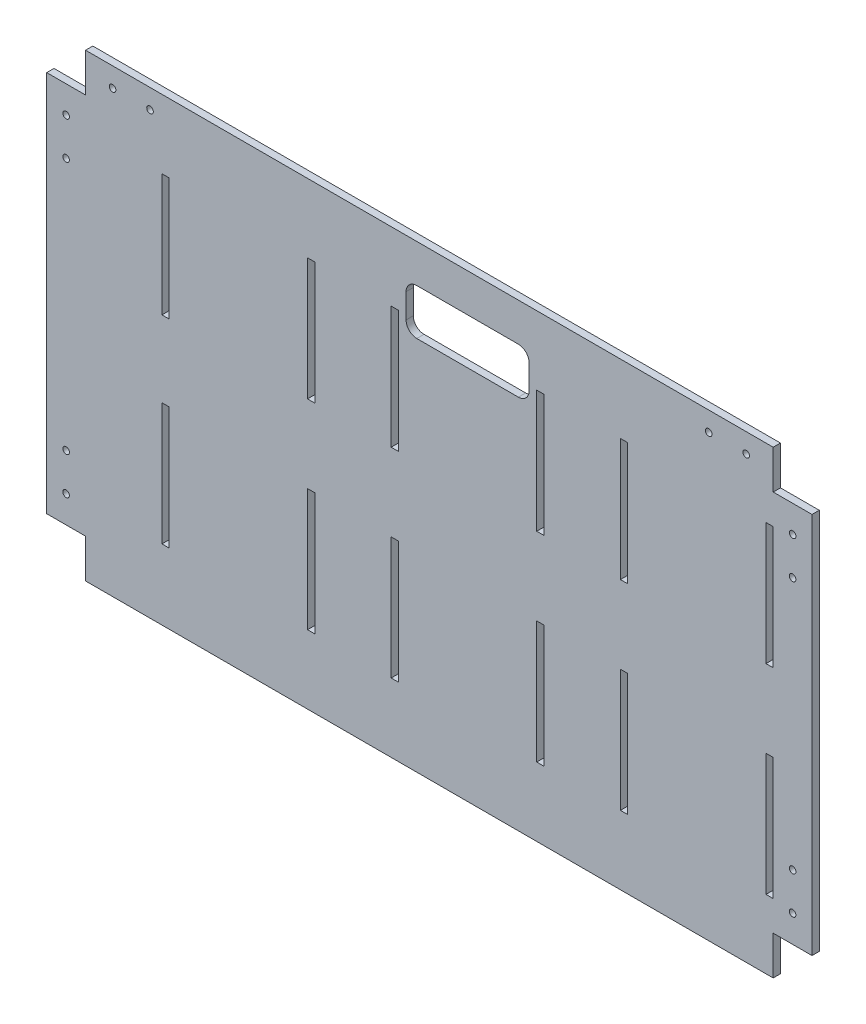
SolidWorks part; units mm, degrees
ref_plane "前基準面" through (0, 0, 0) normal (0, 0, 1) x (1, 0, 0)
ref_plane "上基準面" through (0, 0, 0) normal (0, 1, 0) x (1, 0, 0)
ref_plane "右基準面" through (0, 0, 0) normal (1, 0, 0) x (0, 0, -1)
sketch "草圖1" plane through (0, 0, 0) normal (0, 0, 1) x (1, 0, 0)
  line L1 (-250.4, 150.4) -> (250.4, 150.4)
  line L2 (-250.4, 150.4) -> (-250.4, -150.4)
  line L3 (-250.4, -150.4) -> (250.4, -150.4)
  line L4 (250.4, 150.4) -> (250.4, -150.4)
  line L5 (-250.4, 150.4) -> (250.4, -150.4) construction
  line L6 (-250.4, -150.4) -> (250.4, 150.4) construction
  point P0 (0, 0)
  dimension "D1" = 500.8
  dimension "D2" = 300.8
extrude "填料-伸長1" add sketch "草圖1" along normal blind 4.75 contours L1 L4 L3 L2
sketch "草圖2" plane through (0, 0, 0) normal (0, 0, -1) x (-1, 0, 0)
  line L0 (-225, 125) -> (-225, -125) construction
  line L1 (-250.4, 150.4) -> (-225, 150.4)
  line L2 (-250.4, 150.4) -> (-250.4, 125)
  line L3 (-250.4, 125) -> (-225, 125)
  line L4 (-225, 150.4) -> (-225, 125)
  line L5 (-250.4, -150.4) -> (-225, -150.4)
  line L6 (-250.4, -150.4) -> (-250.4, -125)
  line L7 (-250.4, -125) -> (-225, -125)
  line L8 (-225, -150.4) -> (-225, -125)
  line L9 (250.4, 150.4) -> (225, 150.4)
  line L10 (250.4, 150.4) -> (250.4, 125)
  line L12 (225, 150.4) -> (225, 125)
  line L13 (250.4, -150.4) -> (225, -150.4)
  line L14 (250.4, -150.4) -> (250.4, -125)
  line L16 (225, -150.4) -> (225, -125)
  line L18 (250.4, 150.4) -> (-250.4, 150.4) construction
  line L19 (-225, 105.4) -> (-220.25, 105.4)
  line L20 (-225, 105.4) -> (-225, 25.4)
  line L21 (-225, 25.4) -> (-220.25, 25.4)
  line L22 (-220.25, 105.4) -> (-220.25, 25.4)
  line L23 (-225, -25.4) -> (-220.25, -25.4)
  line L24 (-225, -25.4) -> (-225, -105.4)
  line L25 (-225, -105.4) -> (-220.25, -105.4)
  line L26 (-220.25, -25.4) -> (-220.25, -105.4)
  line L27 (250.4, -150.4) -> (-250.4, -150.4) construction
  line L44 (175, 105.4) -> (175, 25.4)
  line L45 (175, 105.4) -> (170.25, 105.4)
  line L46 (170.25, 105.4) -> (170.25, 25.4)
  line L47 (175, 25.4) -> (170.25, 25.4)
  line L48 (175, -24.4) -> (175, -104.4)
  line L49 (175, -24.4) -> (170.25, -24.4)
  line L50 (170.25, -24.4) -> (170.25, -104.4)
  line L51 (175, -104.4) -> (170.25, -104.4)
  line L52 (-129.75, 105.4) -> (-129.75, 25.4)
  line L53 (-129.75, 25.4) -> (-125, 25.4)
  line L54 (-125, 105.4) -> (-125, 25.4)
  line L55 (-129.75, 105.4) -> (-125, 105.4)
  line L60 (-75, 105.4) -> (-75, 25.4)
  line L61 (-75, 25.4) -> (-70.25, 25.4)
  line L62 (-70.25, 105.4) -> (-70.25, 25.4)
  line L63 (-75, 105.4) -> (-70.25, 105.4)
  line L68 (20.25, 105.4) -> (20.25, 25.4)
  line L69 (20.25, 25.4) -> (25, 25.4)
  line L70 (25, 105.4) -> (25, 25.4)
  line L71 (20.25, 105.4) -> (25, 105.4)
  line L80 (75, 105.4) -> (75, 25.4)
  line L81 (75, 25.4) -> (79.75, 25.4)
  line L82 (79.75, 105.4) -> (79.75, 25.4)
  line L83 (75, 105.4) -> (79.75, 105.4)
  line L84 (-250.4, 0) -> (250.4, 0) construction
  line L85 (-250.4, 150.4) -> (-250.4, -150.4) construction
  line L86 (250.4, 150.4) -> (250.4, -150.4) construction
  line L89 (250.4, -125) -> (250.4, 125)
  line L91 (250.4, 125) -> (250.4, -125)
  line L92 (75, -105.4) -> (79.75, -105.4)
  line L93 (79.75, -105.4) -> (79.75, -25.4)
  line L94 (75, -25.4) -> (79.75, -25.4)
  line L95 (75, -105.4) -> (75, -25.4)
  line L96 (20.25, -105.4) -> (25, -105.4)
  line L97 (25, -105.4) -> (25, -25.4)
  line L98 (20.25, -25.4) -> (25, -25.4)
  line L99 (20.25, -105.4) -> (20.25, -25.4)
  line L101 (-129.75, -105.4) -> (-125, -105.4)
  line L102 (-125, -105.4) -> (-125, -25.4)
  line L103 (-129.75, -25.4) -> (-125, -25.4)
  line L104 (-129.75, -105.4) -> (-129.75, -25.4)
  line L105 (-75, -105.4) -> (-70.25, -105.4)
  line L106 (-70.25, -105.4) -> (-70.25, -25.4)
  line L107 (-75, -25.4) -> (-70.25, -25.4)
  line L108 (-75, -105.4) -> (-75, -25.4)
  line L109 (225, 125) -> (250.4, 125)
  line L110 (225, -125) -> (250.4, -125)
  dimension "D1" = 25.4
  dimension "D2" = 25.4
  dimension "D3" = 25.4
  dimension "D4" = 25.4
  dimension "D5" = 25.4
  dimension "D6" = 25.4
  dimension "D7" = 25.4
  dimension "D8" = 25.4
  dimension "D9" = 4.75
  dimension "D10" = 80
  dimension "D11" = 45
  dimension "D12" = 4.75
  dimension "D13" = 80
  dimension "D14" = 45
  dimension "D16" = 100
  dimension "D17" = 25.4
  dimension "D19" = 250
  dimension "D20" = 50
  dimension "D27" = 50
  dimension "D21" = 4.75
  dimension "D23" = 4.75
  dimension "D28" = 100
  dimension "D24" = 2
  dimension "D25" = 2
  dimension "D26" = 2
extrude "除料-伸長1" cut sketch "草圖2" against normal blind 10
sketch "草圖3" plane through (0, 0, 4.75) normal (0, 0, 1) x (1, 0, 0)
  circle A0 centre (-237.7, 107.3) radius 2.15
  circle A1 centre (-237.7, 82.8) radius 2.15
  circle A2 centre (-207.3, 137.7) radius 2.15
  circle A3 centre (-182.8, 137.7) radius 2.15
  circle A4 centre (-237.7, -82.8) radius 2.15
  circle A5 centre (-237.7, -107.3) radius 2.15
  circle A10 centre (237.7, -107.3) radius 2.15
  circle A11 centre (237.7, -82.8) radius 2.15
  circle A12 centre (237.7, 107.3) radius 2.15
  circle A13 centre (237.7, 82.8) radius 2.15
  circle A14 centre (182.8, 137.7) radius 2.15
  circle A15 centre (207.3, 137.7) radius 2.15
extrude "除料-伸長2" cut sketch "草圖3" against normal blind 5
sketch "草圖4" plane through (0, 0, 4.75) normal (0, 0, 1) x (1, 0, 0)
  line L0 (-225, 150.4) -> (225, 150.4) construction
  line L8 (-15.25, 125.4) -> (65.25, 125.4)
  line L11 (-15.25, 125.4) -> (-15.25, 95.4)
  line L12 (-15.25, 95.4) -> (65.25, 95.4)
  line L13 (65.25, 125.4) -> (65.25, 95.4)
  line L14 (-15.25, 125.4) -> (65.25, 95.4) construction
  line L15 (-15.25, 95.4) -> (65.25, 125.4) construction
  line L16 (-20.25, 25.4) -> (-20.25, 105.4) construction
  point P0 (25, 110.4)
  dimension "D1" = 25
  dimension "D2" = 30
  dimension "D3" = 80.5
  dimension "D4" = 5
extrude "除料-伸長3" cut sketch "草圖4" against normal blind 4.75
fillet "圓角1" radius 7 4 edges at (-15.25, 95.4, 2.375) (65.25, 95.4, 2.375) (65.25, 125.4, 2.375) (-15.25, 125.4, 2.375)
